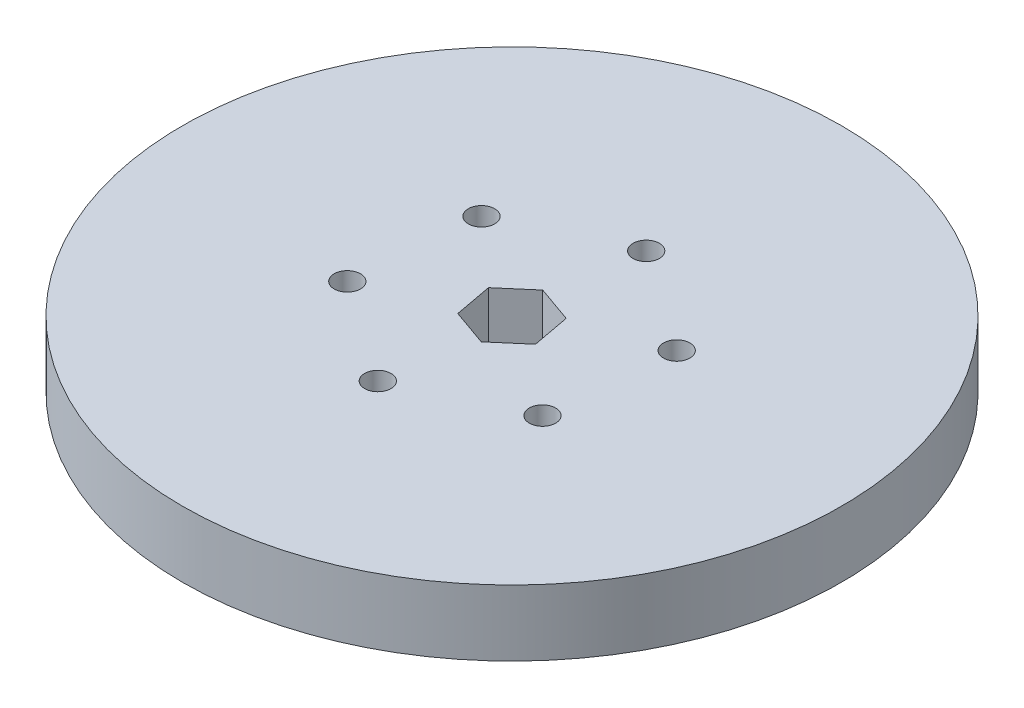
SolidWorks part; units mm, degrees
ref_plane "Front Plane" through (0, 0, 0) normal (0, 0, 1) x (1, 0, 0)
ref_plane "Top Plane" through (0, 0, 0) normal (0, 1, 0) x (1, 0, 0)
ref_plane "Right Plane" through (0, 0, 0) normal (1, 0, 0) x (0, 0, -1)
sketch "Sketch1" plane through (0, 0, 0) normal (0, 1, 0) x (1, 0, 0)
  circle A0 centre (0, 0) radius 63.5
  dimension "D1" = 127
extrude "Boss-Extrude1" add sketch "Sketch1" against normal blind 12.7
sketch "Sketch7" plane through (0, 0, 0) normal (0, 1, 0) x (1, 0, 0)
  circle A6 centre (19.563, -13.6877) radius 2.54
  circle A8 centre (21.6354, 10.0982) radius 2.54
  circle A9 centre (2.0724, 23.7859) radius 2.54
  circle A10 centre (-19.563, 13.6877) radius 2.54
  circle A11 centre (-21.6354, -10.0982) radius 2.54
  circle A12 centre (-2.0724, -23.7859) radius 2.54
  point P15 (0, 0)
  dimension "D1" = 23.876
  dimension "D2" = 6
extrude "Cut-Extrude2" cut sketch "Sketch7" against normal through all
sketch "Sketch8" plane through (0, 0, 0) normal (0, 1, 0) x (1, 0, 0)
  line L1 (-5.6235, -4.8188) -> (1.3614, -7.2795)
  line L2 (1.3614, -7.2795) -> (6.9849, -2.4607)
  line L3 (6.9849, -2.4607) -> (5.6235, 4.8188)
  line L4 (5.6235, 4.8188) -> (-1.3614, 7.2795)
  line L5 (-1.3614, 7.2795) -> (-6.9849, 2.4607)
  line L6 (-6.9849, 2.4607) -> (-5.6235, -4.8188)
  circle A0 centre (0, 0) radius 6.4135 construction
  point P1 (0, 0)
  point P11 (-5.6235, 2.4607)
  point P12 (0, 0)
  dimension "D1" = 12.827
extrude "Cut-Extrude3" cut sketch "Sketch8" against normal through all
